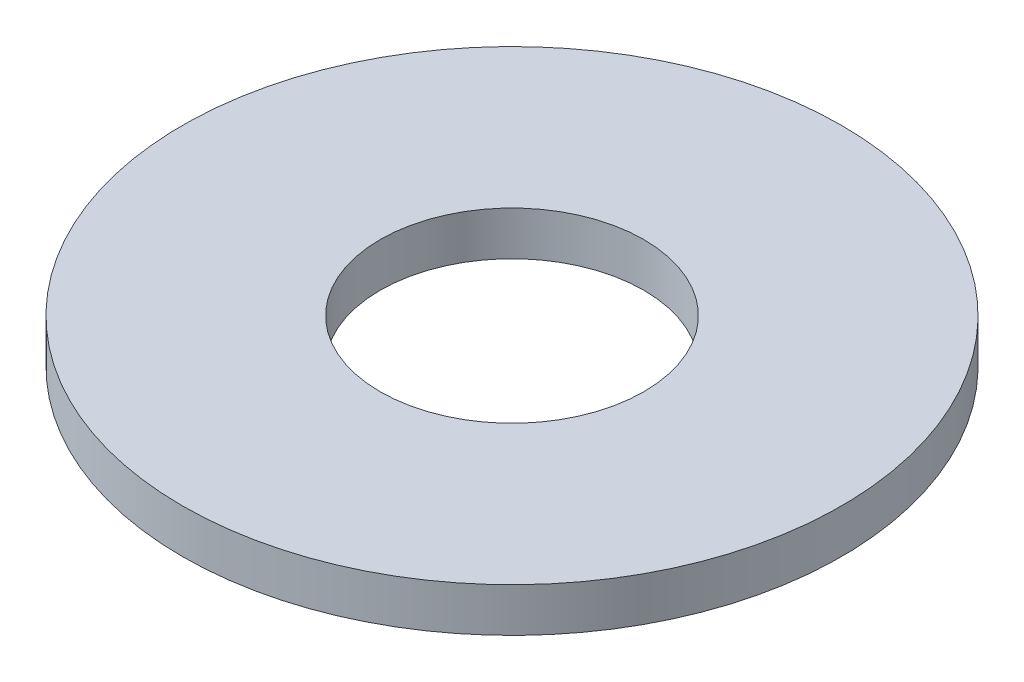
SolidWorks part; units mm, degrees
ref_plane "Plano frontal" through (0, 0, 0) normal (0, 0, 1) x (1, 0, 0)
ref_plane "Plano superior" through (0, 0, 0) normal (0, 1, 0) x (1, 0, 0)
ref_plane "Plano direito" through (0, 0, 0) normal (1, 0, 0) x (0, 0, -1)
sketch "Esboço1" plane through (0, 0, 0) normal (0, 1, 0) x (1, 0, 0)
  circle A0 centre (0, 0) radius 7.5
  circle A1 centre (0, 0) radius 3
  dimension "D1" = 15
  dimension "D2" = 6
extrude "Ressalto-extrusão1" add sketch "Esboço1" along normal blind 1
